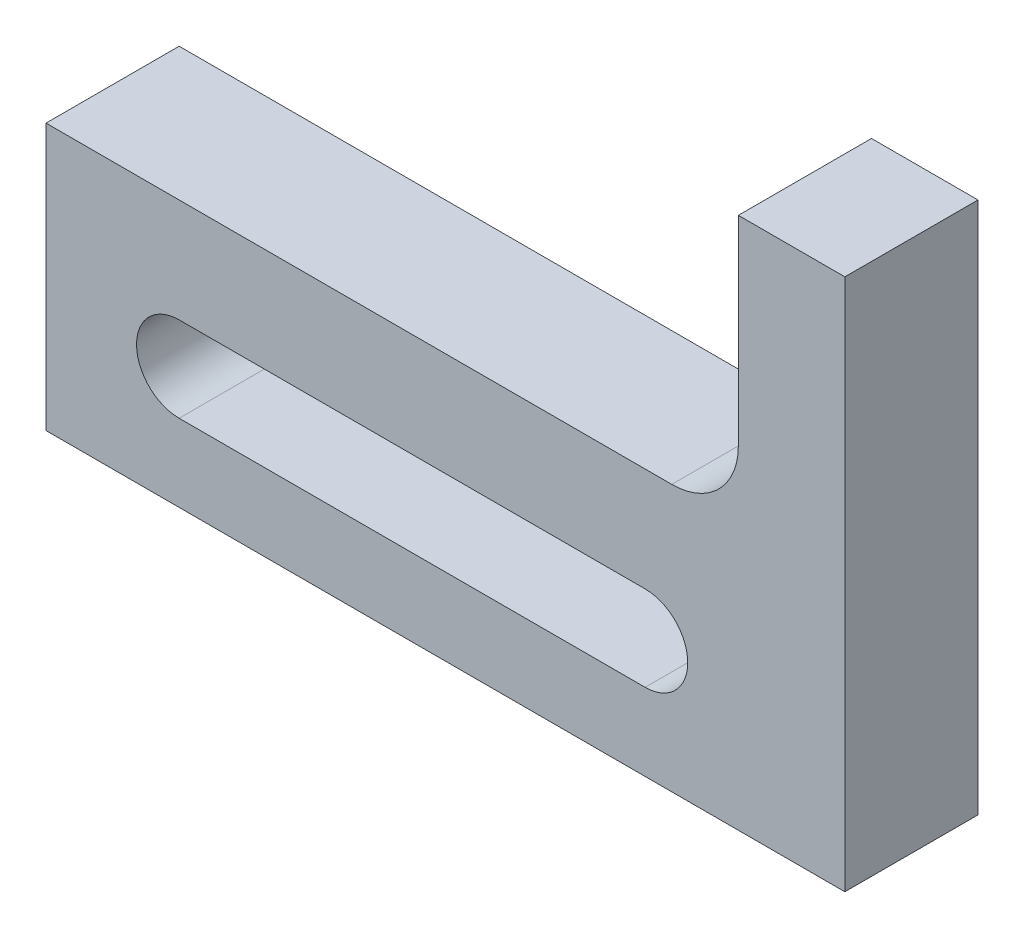
SolidWorks part; units mm, degrees
material "SKD11淬火HRC56-60"
ref_plane "前基準面" through (0, 0, 0) normal (0, 0, 1) x (1, 0, 0)
ref_plane "上基準面" through (0, 0, 0) normal (0, 1, 0) x (1, 0, 0)
ref_plane "右基準面" through (0, 0, 0) normal (1, 0, 0) x (0, 0, -1)
sketch "草图1" plane through (0, 0, 0) normal (0, 0, 1) x (1, 0, 0)
  line L1 (0, 0) -> (60, 0)
  line L2 (0, 0) -> (0, 40)
  line L3 (0, 40) -> (60, 40)
  line L4 (60, 0) -> (60, 40)
  dimension "D1" = 60
  dimension "D2" = 40
extrude "凸台-拉伸1" add sketch "草图1" along normal blind 10
sketch "草图2" plane through (0, 0, 10) normal (0, 0, 1) x (1, 0, 0)
  line L0 (60, 0) -> (60, 40) construction
  line L1 (0, 40) -> (52, 40)
  line L2 (0, 40) -> (0, 20)
  line L3 (0, 20) -> (52, 20)
  line L4 (52, 40) -> (52, 20)
  dimension "D1" = 8
  dimension "D2" = 20
extrude "切除-拉伸1" cut sketch "草图2" against normal through all
fillet "圆角1" radius 5 1 edges at (52, 20, 5)
sketch "草图3" plane through (0, 0, 10) normal (0, 0, 1) x (1, 0, 0)
  line L0 (10, 9) -> (45, 9) construction
  line L1 (10, 12.2) -> (45, 12.2)
  line L2 (10, 5.8) -> (45, 5.8)
  line L3 (0, 0) -> (60, 0) construction
  line L4 (0, 20) -> (0, 0) construction
  arc A0 (10, 12.2) -> (10, 5.8) centre (10, 9) ccw
  arc A1 (45, 5.8) -> (45, 12.2) centre (45, 9) ccw
  point P2 (27.5, 9)
  dimension "D3" = 10
  dimension "D1" = 6.4
  dimension "D2" = 9
  dimension "D4" = 35
extrude "切除-拉伸2" cut sketch "草图3" against normal through all
